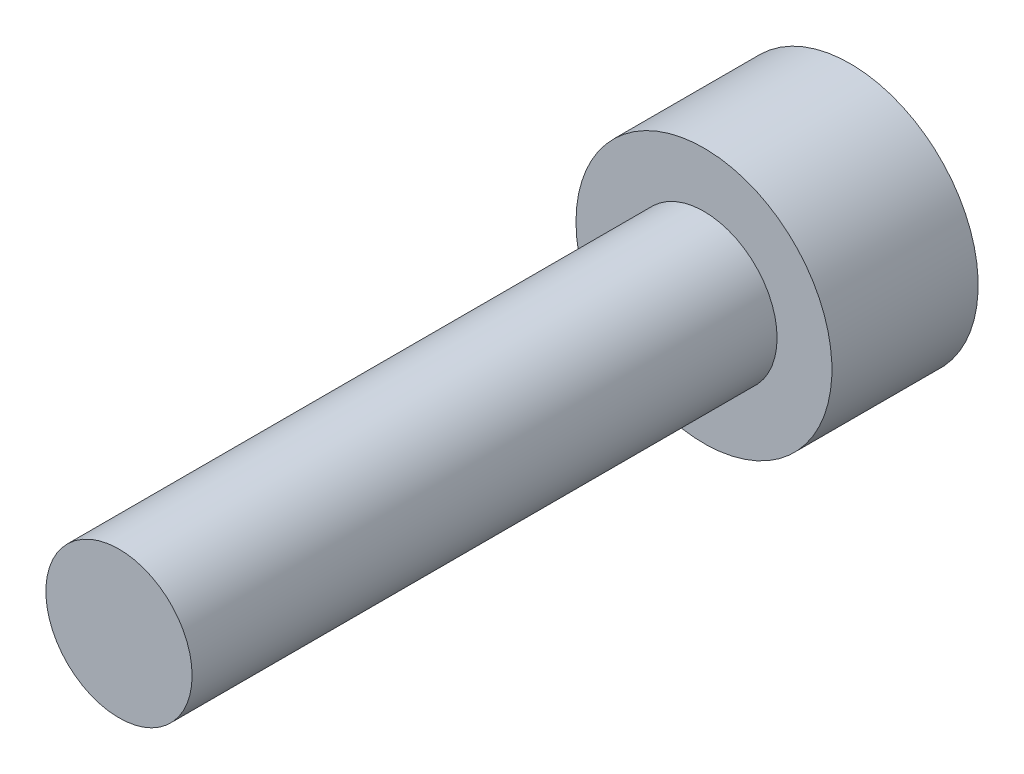
SolidWorks part; units mm, degrees
ref_plane "Front Plane" through (0, 0, 0) normal (0, 0, 1) x (1, 0, 0)
ref_plane "Top Plane" through (0, 0, 0) normal (0, 1, 0) x (1, 0, 0)
ref_plane "Right Plane" through (0, 0, 0) normal (1, 0, 0) x (0, 0, -1)
ref_plane "Plane1" through (0, 0, 0) normal (0, -1, 0) x (1, 0, 0)
sketch "Sketch1" plane through (0, 0, 0) normal (0, -1, 0) x (1, 0, 0)
  line L0 (3.5, 4) -> (0, 4)
  line L1 (0, 4) -> (0, 0)
  line L2 (0, 0) -> (3.5, 0)
  line L3 (3.5, 0) -> (3.5, 4)
  line L4 (0, 4) -> (0, 0) construction
revolve "Revolve1" add sketch "Sketch1" angle 360 about L4
sketch "Sketch2" plane through (0, 0, 4) normal (0, 0, 1) x (1, 0, 0)
  circle A0 centre (0, 0) radius 2
extrude "Boss-Extrude1" add sketch "Sketch2" along normal blind 16
sketch "Sketch3" plane through (0, 0, 0) normal (0, 0, -1) x (-1, 0, 0)
  line L0 (-1.7, 0) -> (-0.85, -1.4722)
  line L1 (-0.85, -1.4722) -> (0.85, -1.4722)
  line L2 (0.85, -1.4722) -> (1.7, 0)
  line L3 (1.7, 0) -> (0.85, 1.4722)
  line L4 (0.85, 1.4722) -> (-0.85, 1.4722)
  line L5 (-0.85, 1.4722) -> (-1.7, 0)
extrude "Cut-Extrude1" cut sketch "Sketch3" against normal blind 2.4
